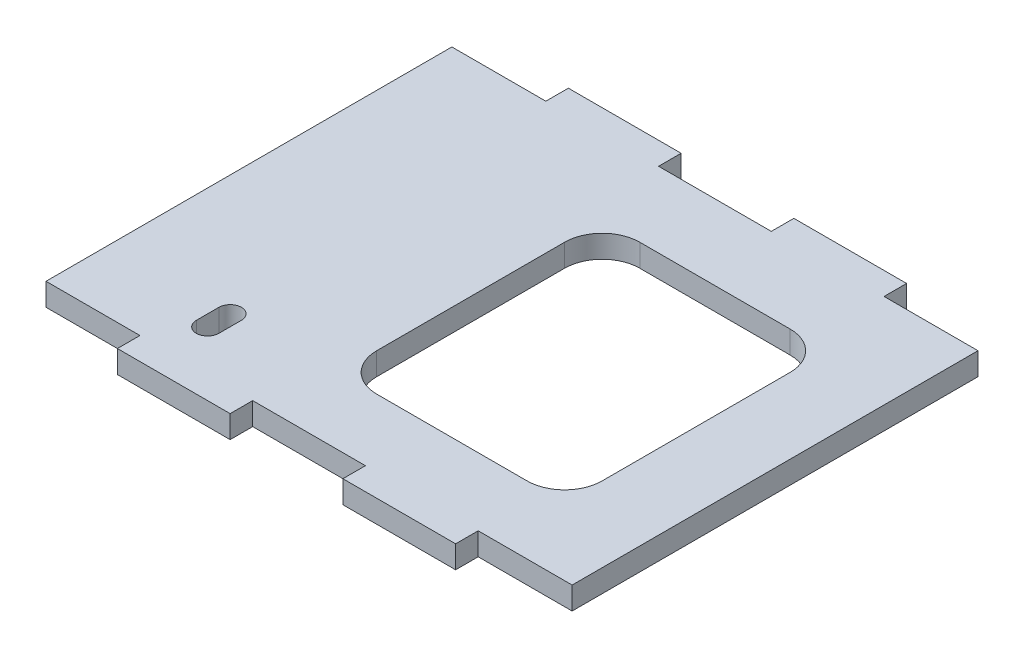
SolidWorks part; units mm, degrees
material "ABS PC"
ref_plane "Front Plane" through (0, 0, 0) normal (0, 0, 1) x (1, 0, 0)
ref_plane "Top Plane" through (0, 0, 0) normal (0, 1, 0) x (1, 0, 0)
ref_plane "Right Plane" through (0, 0, 0) normal (1, 0, 0) x (0, 0, -1)
sketch "Sketch1" plane through (0, 0, 0) normal (0, 1, 0) x (1, 0, 0)
  line L0 (-35, 27) -> (-22.5, 27)
  line L1 (-22.5, 27) -> (-22.5, 30)
  line L2 (-22.5, 30) -> (-7.5, 30)
  line L3 (-7.5, 30) -> (-7.5, 27)
  line L4 (-7.5, 27) -> (7.5, 27)
  line L5 (7.5, 27) -> (7.5, 30)
  line L6 (7.5, 30) -> (22.5, 30)
  line L7 (22.5, 30) -> (22.5, 27)
  line L8 (22.5, 27) -> (35, 27)
  line L9 (35, 27) -> (35, -27)
  line L10 (35, -27) -> (22.5, -27)
  line L11 (22.5, -27) -> (22.5, -30)
  line L12 (22.5, -30) -> (7.5, -30)
  line L13 (7.5, -30) -> (7.5, -27)
  line L14 (7.5, -27) -> (-7.5, -27)
  line L15 (-7.5, -27) -> (-7.5, -30)
  line L16 (-7.5, -30) -> (-22.5, -30)
  line L17 (-22.5, -30) -> (-22.5, -27)
  line L18 (-22.5, -27) -> (-35, -27)
  line L19 (-35, -27) -> (-35, 27)
  line L20 (-35, 0) -> (0, 0) construction
  line L21 (0, 0) -> (35, 0) construction
  dimension "D1" = 70
  dimension "D2" = 3
  dimension "D3" = 15
  dimension "D4" = 60
extrude "Boss-Extrude1" add sketch "Sketch1" along normal blind 3
sketch "Sketch2" plane through (0, 3, 0) normal (0, 1, 0) x (1, 0, 0)
  line L0 (35, -27) -> (35, 27) construction
  line L1 (0, 17) -> (20, 17)
  line L2 (-5, 12) -> (-5, -13)
  line L4 (0, -18) -> (20, -18)
  line L5 (25, 12) -> (25, -13)
  line L6 (22.5, -27) -> (7.5, -27) construction
  arc A0 (20, 17) -> (25, 12) centre (20, 12) cw
  arc A1 (25, -13) -> (20, -18) centre (20, -13) cw
  arc A2 (0, -18) -> (-5, -13) centre (0, -13) cw
  arc A3 (-5, 12) -> (0, 17) centre (0, 12) cw
  dimension "D1" = 5
  dimension "D2" = 30
  dimension "D3" = 35
  dimension "D4" = 10
  dimension "D5" = 9
extrude "Cut-Extrude1" cut sketch "Sketch2" against normal through all
sketch "Sketch4" plane through (0, 3, 0) normal (0, 1, 0) x (1, 0, 0)
  line L0 (-19, -18.5) -> (-19, -21.5) construction
  line L1 (-17.5, -18.5) -> (-17.5, -21.5)
  line L2 (-20.5, -18.5) -> (-20.5, -21.5)
  line L3 (-22.5, -27) -> (-7.5, -27) construction
  line L4 (-35, 27) -> (-35, -27) construction
  arc A0 (-17.5, -18.5) -> (-20.5, -18.5) centre (-19, -18.5) ccw
  arc A1 (-20.5, -21.5) -> (-17.5, -21.5) centre (-19, -21.5) ccw
  point P2 (-19, -20)
  dimension "D2" = 1.5
  dimension "D1" = 3
  dimension "D3" = 5.5
  dimension "D4" = 14.5
extrude "Cut-Extrude3" cut sketch "Sketch4" against normal through all
